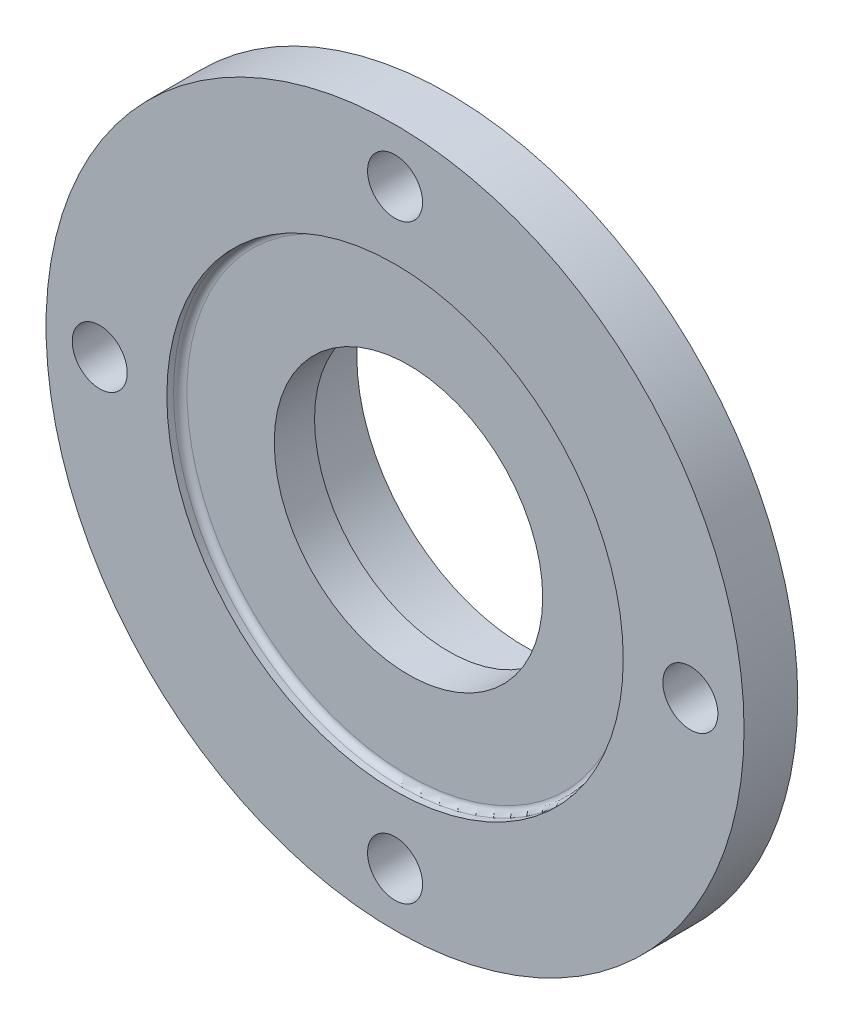
SolidWorks part; units mm, degrees
ref_plane "Спереди" through (0, 0, 0) normal (0, 0, 1) x (1, 0, 0)
ref_plane "Сверху" through (0, 0, 0) normal (0, 1, 0) x (1, 0, 0)
ref_plane "Справа" through (0, 0, 0) normal (1, 0, 0) x (0, 0, -1)
sketch "Эскиз1" plane through (0, 0, 0) normal (0, 0, 1) x (1, 0, 0)
  circle A0 centre (0, 0) radius 52
  circle A1 centre (0, 44) radius 4.1
  circle A2 centre (44, 0) radius 4.1
  circle A3 centre (0, -44) radius 4.1
  circle A4 centre (-44, 0) radius 4.1
  point P14 (0, 0)
  dimension "D1" = 104
  dimension "D2" = 8.2
  dimension "D3" = 44
  dimension "D4" = 4
extrude "Бобышка-Вытянуть1" add sketch "Эскиз1" along normal blind 8
sketch "Эскиз2" plane through (0, 0, 8) normal (0, 0, 1) x (1, 0, 0)
  circle A0 centre (0, 0) radius 34
  dimension "D1" = 68
extrude "Вырез-Вытянуть1" cut sketch "Эскиз2" against normal blind 2
fillet "Скругление1" radius 1 1 edges at (34, 0, 6)
sketch "Эскиз3" plane through (0, 0, 0) normal (0, 0, -1) x (-1, 0, 0)
  circle A0 centre (0, 0) radius 34
  circle A1 centre (0, 0) radius 25
  dimension "D1" = 68
  dimension "D2" = 50
extrude "Бобышка-Вытянуть2" add sketch "Эскиз3" along normal blind 11.3
chamfer "Фаска1" distance 0.4 angle 45 1 edges at (-25, 0, 0)
sketch "Эскиз4" plane through (0, 0, 0) normal (0, 0, -1) x (-1, 0, 0)
  circle A0 centre (0, 0) radius 20
  dimension "D1" = 40
extrude "Вырез-Вытянуть2" cut sketch "Эскиз4" against normal blind 10
